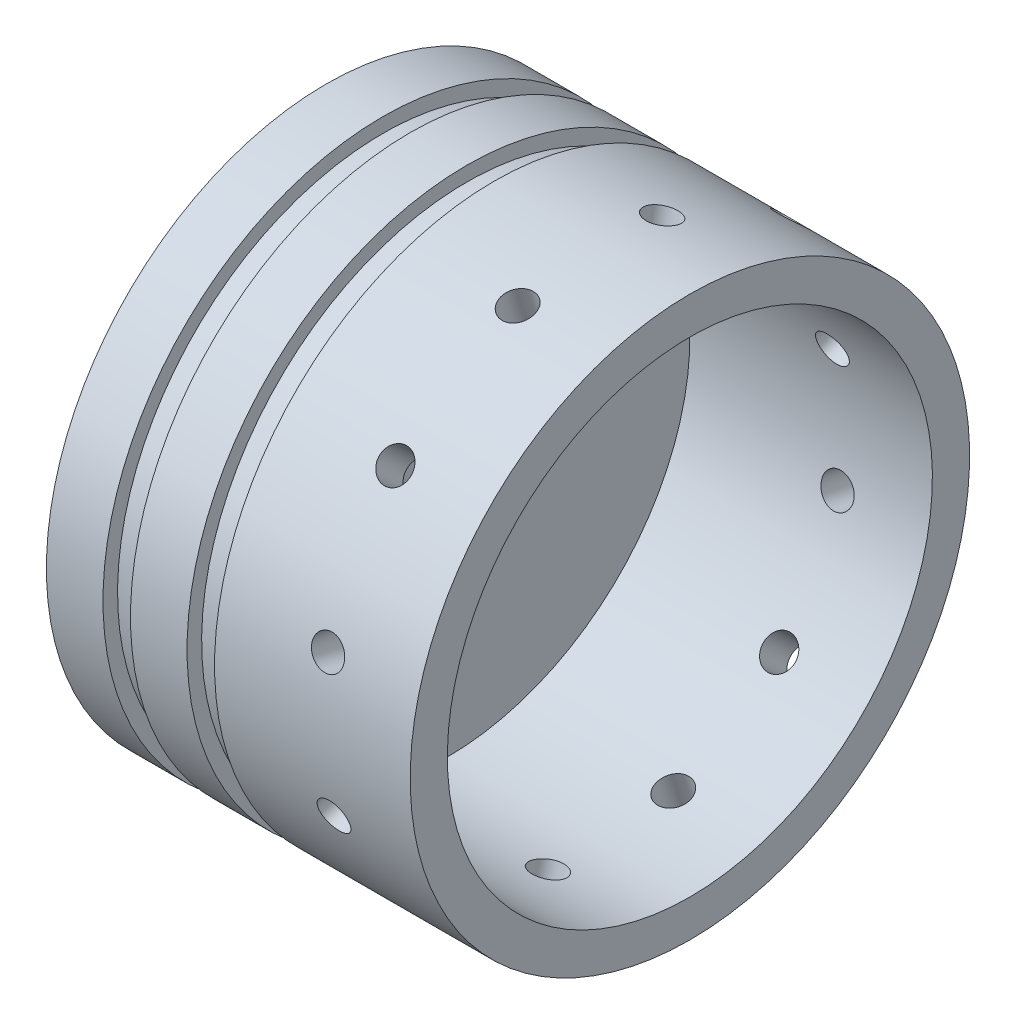
SolidWorks part; units mm, degrees
ref_plane "Front Plane" through (0, 0, 0) normal (0, 0, 1) x (1, 0, 0)
ref_plane "Top Plane" through (0, 0, 0) normal (0, 1, 0) x (1, 0, 0)
ref_plane "Right Plane" through (0, 0, 0) normal (1, 0, 0) x (0, 0, -1)
sketch "Sketch1" plane through (0, 0, 0) normal (0, 0, 1) x (1, 0, 0)
  line L0 (13.208, 43.942) -> (22.098, 43.942)
  line L1 (0, 0) -> (19.05, 0)
  line L2 (0, 0) -> (0, 43.942)
  line L3 (0, 43.942) -> (8.89, 43.942)
  line L4 (57.15, 38.1) -> (57.15, 43.942)
  line L7 (57.15, 38.1) -> (19.05, 38.1)
  line L8 (19.05, 0) -> (19.05, 38.1)
  line L10 (8.89, 43.942) -> (8.89, 41.656)
  line L11 (8.89, 41.656) -> (13.208, 41.656)
  line L12 (13.208, 43.942) -> (13.208, 41.656)
  line L14 (22.098, 43.942) -> (22.098, 41.656)
  line L15 (22.098, 41.656) -> (26.416, 41.656)
  line L16 (26.416, 43.942) -> (26.416, 41.656)
  line L17 (26.416, 43.942) -> (57.15, 43.942)
  point P11 (9.525, 0)
  dimension "D1" = 43.942
  dimension "D2" = 57.15
  dimension "D3" = 38.1
  dimension "D4" = 38.1
  dimension "D5" = 41.656
  dimension "D6" = 4.318
  dimension "D7" = 8.89
  dimension "D8" = 4.318
  dimension "D9" = 8.89
  dimension "D10" = 41.656
revolve "Revolve1" add sketch "Sketch1" angle 360 about L1
hole_wizard "1/4-20 Tapped Hole1" positions "3DSketch1" profile "Sketch2" tap size "1/4-20" standard "ANSI Inch"
sketch3d "3DSketch1"
  point P0 (43.18, 41.9439, 13.0999)
  dimension "D1" = 13.97
sketch "Sketch2" plane through (43.18, 41.9439, 13.0999) normal (1, 0, 0) x (0, -0.2981, 0.9545)
  line L0 (0, 0) -> (0, 45.4748)
  line L1 (0, 45.4748) -> (2.5527, 43.941)
  line L2 (2.5527, 43.941) -> (2.5527, 0)
  line L5 (2.5527, 0) -> (0, 0)
  line L10 (0, 45.4748) -> (-2.5527, 43.941) construction
  line L11 (0, -6.35) -> (0, 107.95) construction
  dimension "Tap Drill Dia." = 5.1054
  dimension "Tap Drill Depth" = 43.941
  dimension "Drill Angle" = 118
pattern_circular "CirPattern1" count 12 over 360 about axis through (57.15, 0, 0) along (-1, 0, 0) of "1/4-20 Tapped Hole1"
